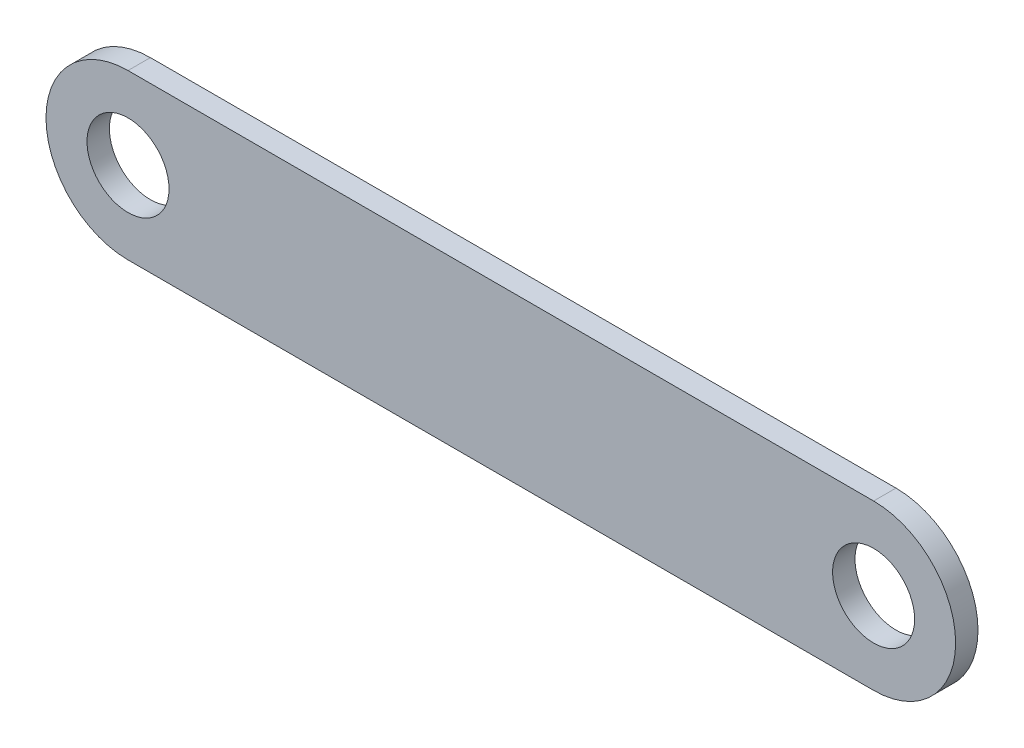
SolidWorks part; units mm, degrees
ref_plane "Front Plane" through (0, 0, 0) normal (0, 0, 1) x (1, 0, 0)
ref_plane "Top Plane" through (0, 0, 0) normal (0, 1, 0) x (1, 0, 0)
ref_plane "Right Plane" through (0, 0, 0) normal (1, 0, 0) x (0, 0, -1)
sketch "Sketch1" plane through (0, 0, 0) normal (0, 0, 1) x (1, 0, 0)
  line L0 (-100, 0) -> (100, 0) construction
  line L1 (-100, 22) -> (100, 22)
  line L2 (-100, -22) -> (100, -22)
  arc A0 (-100, 22) -> (-100, -22) centre (-100, 0) ccw
  arc A1 (100, -22) -> (100, 22) centre (100, 0) ccw
  circle A2 centre (100, 0) radius 11
  circle A3 centre (-100, 0) radius 11
  point P2 (0, 0)
  dimension "D2" = 22
  dimension "D3" = 22
  dimension "D4" = 22
  dimension "D1" = 200
extrude "Boss-Extrude3" add sketch "Sketch1" along normal blind 6
